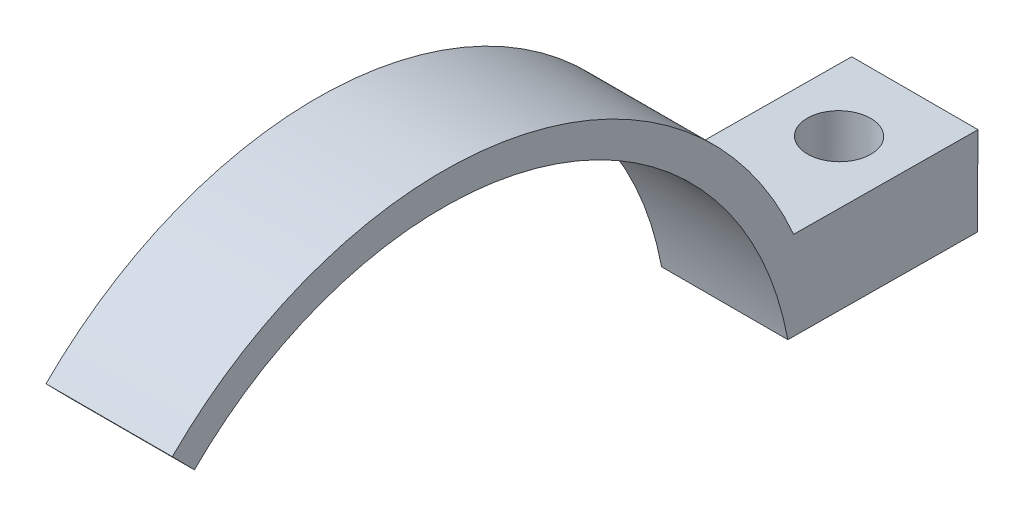
SolidWorks part; units mm, degrees
ref_plane "Front Plane" through (0, 0, 0) normal (0, 0, 1) x (1, 0, 0)
ref_plane "Top Plane" through (0, 0, 0) normal (0, 1, 0) x (1, 0, 0)
ref_plane "Right Plane" through (0, 0, 0) normal (1, 0, 0) x (0, 0, -1)
sketch "Sketch5" plane through (0, 0, 0) normal (1, 0, 0) x (0, 0, -1)
  line L1 (-19.6635, 19.6341) -> (-21.4165, 21.4165)
  line L2 (27.3216, 5.0678) -> (29.8641, 5.0467)
  arc A0 (27.3216, 5.0678) -> (-19.6635, 19.6341) centre (0, 0) ccw
  arc A1 (29.8641, 5.0467) -> (-21.4165, 21.4165) centre (0, 0) ccw
  point P3 (0, 0)
  dimension "D1" = 55.5752
  dimension "D2" = 60.575
  dimension "D3" = 135
  dimension "D4" = 2.5
  dimension "D5" = 2.5426
extrude "Boss-Extrude1" add sketch "Sketch5" along normal mid plane 10
sketch "Sketch6" plane through (0, 5.2942, -0.0439) normal (0, -1, 0.0083) x (1, 0, 0)
  line L1 (-5, -27.2786) -> (5, -27.2786)
  line L2 (-5, -27.2786) -> (-5, -42.2786)
  line L3 (-5, -42.2786) -> (5, -42.2786)
  line L4 (5, -27.2786) -> (5, -42.2786)
  circle A0 centre (0, -36.2786) radius 2.5
  dimension "D4" = 5
  dimension "D1" = 15
  dimension "D2" = 10
  dimension "D3" = 9
  dimension "D5" = 5
extrude "Boss-Extrude2" add sketch "Sketch6" against normal blind 7
